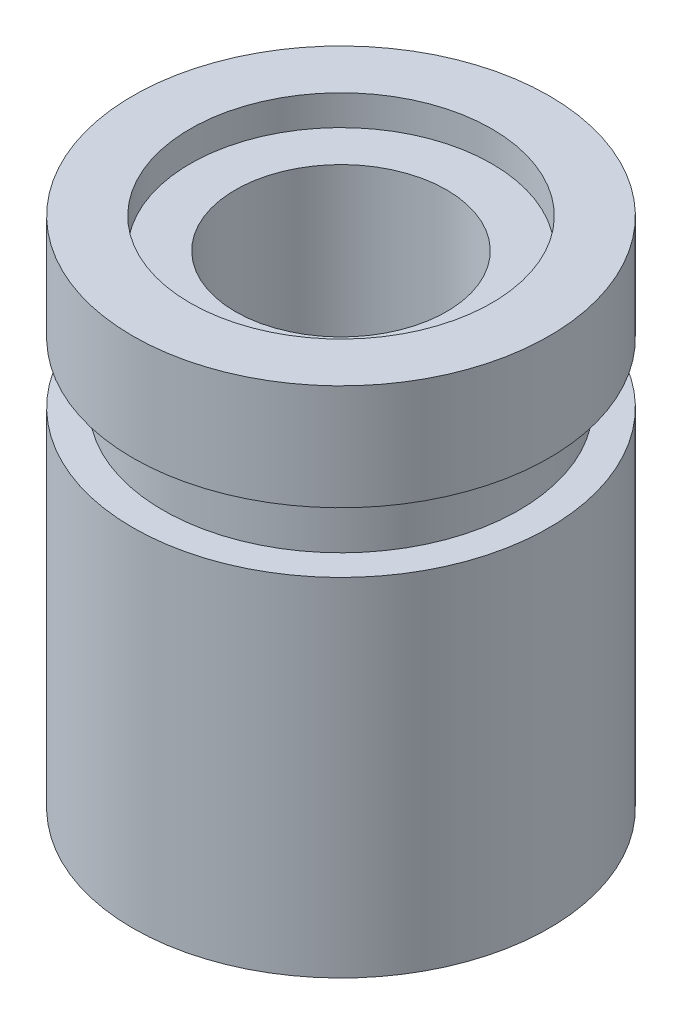
SolidWorks part; units mm, degrees
ref_plane "前视基准面" through (0, 0, 0) normal (0, 0, 1) x (1, 0, 0)
ref_plane "上视基准面" through (0, 0, 0) normal (0, 1, 0) x (1, 0, 0)
ref_plane "右视基准面" through (0, 0, 0) normal (1, 0, 0) x (0, 0, -1)
sketch "草图1" plane through (0, 0, 0) normal (0, 1, 0) x (1, 0, 0)
  circle A0 centre (0, 0) radius 6.9
  circle A1 centre (0, 0) radius 2.5
  dimension "D1" = 13.8
  dimension "D2" = 5
extrude "凸台-拉伸1" add sketch "草图1" along normal blind 17
sketch "草图2" plane through (0, 17, 0) normal (0, 1, 0) x (1, 0, 0)
  circle A0 centre (0, 0) radius 3.5
  dimension "D1" = 7
extrude "切除-拉伸1" cut sketch "草图2" against normal blind 8.5
sketch "草图3" plane through (0, 17, 0) normal (0, 1, 0) x (1, 0, 0)
  circle A0 centre (0, 0) radius 5
  dimension "D1" = 10
extrude "切除-拉伸2" cut sketch "草图3" against normal blind 1
sketch "草图4" plane through (0, 0, 0) normal (0, 0, 1) x (1, 0, 0)
  line L0 (5, 17) -> (-5, 17) construction
  line L1 (5.9, 13.5) -> (7.9728, 13.5)
  line L2 (5.9, 13.5) -> (5.9, 11.5)
  line L3 (5.9, 11.5) -> (7.9728, 11.5)
  line L4 (7.9728, 13.5) -> (7.9728, 11.5)
  line L5 (6.9, 0) -> (6.9, 17) construction
  dimension "D1" = 2
  dimension "D2" = 3.5
  dimension "D3" = 1
sketch "草图5" plane through (0, 0, 0) normal (0, 0, 1) x (1, 0, 0)
  line L0 (0, 0) -> (0, 9.2522) construction
revolve "切除-旋转1" cut sketch "草图4" angle 360 about L0
